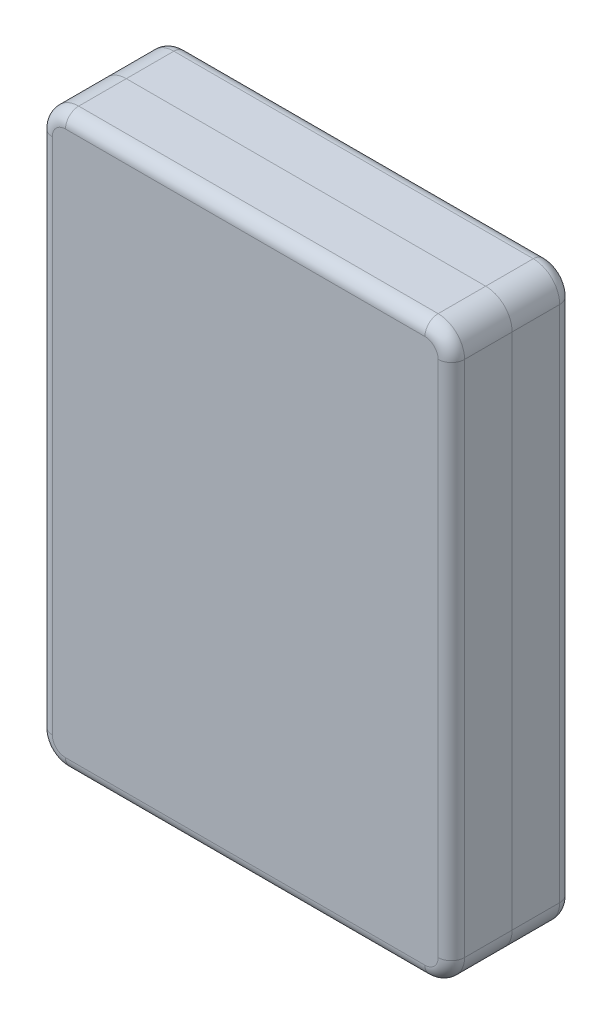
SolidWorks part; units mm, degrees
ref_plane "Front Plane" through (0, 0, 0) normal (0, 0, 1) x (1, 0, 0)
ref_plane "Top Plane" through (0, 0, 0) normal (0, 1, 0) x (1, 0, 0)
ref_plane "Right Plane" through (0, 0, 0) normal (1, 0, 0) x (0, 0, -1)
sketch "Sketch1" plane through (0, 0, 0) normal (0, 0, 1) x (1, 0, 0)
  line L0 (-35, 50) -> (-35, -50) construction
  line L1 (-39, -54) -> (39, -54)
  line L2 (-39, -54) -> (-39, 54)
  line L3 (-39, 54) -> (39, 54)
  line L4 (39, -54) -> (39, 54)
  line L5 (-39, -54) -> (39, 54) construction
  line L6 (-39, 54) -> (39, -54) construction
  line L7 (35, 50) -> (-35, 50) construction
  point P0 (0, 0)
  point P10 (0, 50)
  point P13 (0, 0)
  point P14 (-50.1105, 16.9462)
  dimension "D1" = 4
  dimension "D2" = 4
extrude "Main Shape" add sketch "Sketch1" along normal mid plane 23
sketch "Sketch2" plane through (0, 0, 0) normal (1, 0, 0) x (0, 0, -1)
  line L0 (0, -65) -> (0, 65)
  point P4 (0, 0)
  dimension "D1" = 130
fillet "Fillet1" radius 5 4 edges at (39, -54, 0) (-39, -54, 0) (-39, 54, 0) (39, 54, 0)
fillet "Fillet2" radius 2.5 16 edges at (-37.5355, -52.5355, 11.5) (-39, 0, 11.5) (-37.5355, 52.5355, 11.5) (0, 54, 11.5) (37.5355, 52.5355, 11.5) (39, 0, 11.5) (37.5355, -52.5355, 11.5) (0, -54, 11.5) (37.5355, 52.5355, -11.5) (0, 54, -11.5) (-37.5355, 52.5355, -11.5) (-39, 0, -11.5) (-37.5355, -52.5355, -11.5) (0, -54, -11.5) (37.5355, -52.5355, -11.5) (39, 0, -11.5)
shell "Shell1" thickness 3
split "Split1" trim tools "Sketch2" bodies to split 101 resulting bodies 102 103
